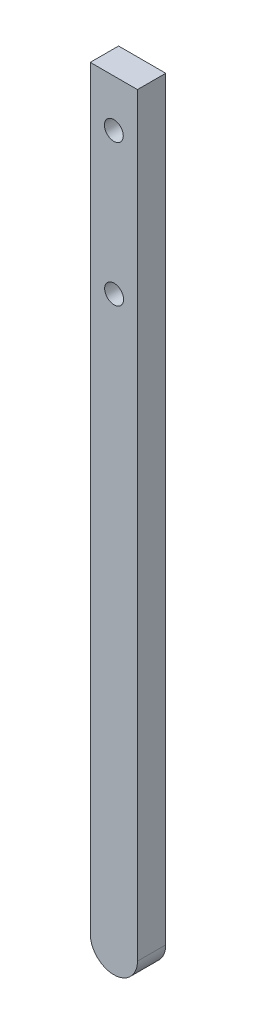
SolidWorks part; units mm, degrees
ref_plane "Front Plane" through (0, 0, 0) normal (0, 0, 1) x (1, 0, 0)
ref_plane "Top Plane" through (0, 0, 0) normal (0, 1, 0) x (1, 0, 0)
ref_plane "Right Plane" through (0, 0, 0) normal (1, 0, 0) x (0, 0, -1)
sketch "Sketch1" plane through (0, 0, 0) normal (0, 0, 1) x (1, 0, 0)
  line L1 (2.5, 40) -> (-2.5, 40)
  line L2 (2.5, 40) -> (2.5, -40)
  line L3 (2.5, -40) -> (-2.5, -40) construction
  line L4 (-2.5, 40) -> (-2.5, -40)
  line L5 (2.5, 40) -> (-2.5, -40) construction
  line L6 (2.5, -40) -> (-2.5, 40) construction
  arc A0 (-2.5, -40) -> (2.5, -40) centre (0, -40) ccw
  circle A1 centre (0, 35) radius 1 construction
  point P0 (0, 0)
  point P11 (-0.9664, 40)
  dimension "D3" = 2
  dimension "D1" = 80
  dimension "D2" = 5
  dimension "D4" = 2.5
  dimension "D5" = 5
extrude "Boss-Extrude1" add sketch "Sketch1" along normal blind 3
sketch "Sketch2" plane through (0, 0, 3) normal (0, 0, 1) x (1, 0, 0)
  line L0 (-2.5, 40) -> (-2.5, -40) construction
  line L1 (2.5, 40) -> (-2.5, 40) construction
  circle A0 centre (0, 35) radius 1
  circle A1 centre (0.0255, 20) radius 1
  dimension "D1" = 2
  dimension "D2" = 2.5
  dimension "D3" = 5
  dimension "D4" = 15
extrude "Cut-Extrude1" cut sketch "Sketch2" against normal through all
